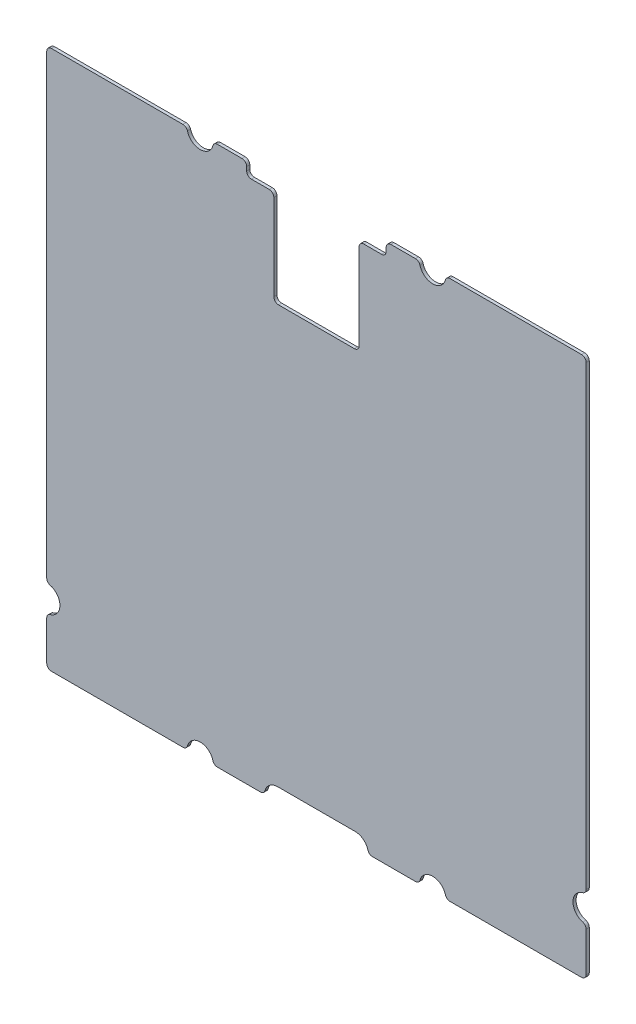
SolidWorks part; units mm, degrees
ref_plane "Front Plane" through (0, 0, 0) normal (0, 0, 1) x (1, 0, 0)
ref_plane "Top Plane" through (0, 0, 0) normal (0, 1, 0) x (1, 0, 0)
ref_plane "Right Plane" through (0, 0, 0) normal (1, 0, 0) x (0, 0, -1)
sketch "Sketch2" plane through (0, 0, 0) normal (0, 0, 1) x (1, 0, 0)
  line L0 (-25, -165.5) -> (25, -165.5)
  line L1 (-174, 174) -> (-83.5, 174)
  line L2 (-174, 174) -> (-174, -126)
  line L3 (-174, -174) -> (-83.5, -174)
  line L4 (174, 174) -> (174, -126)
  line L5 (-174, 174) -> (174, -174) construction
  line L6 (-174, -174) -> (174, 174) construction
  line L7 (33.5, -174) -> (66.5, -174)
  line L8 (-75, -174) -> (75, -174) construction
  line L9 (-66.5, -174) -> (-33.5, -174)
  line L10 (83.5, -174) -> (174, -174)
  line L11 (174, -143) -> (174, -174)
  line L12 (-174, -143) -> (-174, -174)
  line L13 (-66.5, 174) -> (-45, 174)
  line L14 (45, 174) -> (66.5, 174)
  line L15 (83.5, 174) -> (174, 174)
  line L16 (-27.5, 165.5) -> (-27.5, 104)
  line L17 (-25, -174) -> (25, -174) construction
  line L18 (-177.5, 177.5) -> (177.5, 177.5) construction
  line L19 (-177.5, 177.5) -> (-177.5, -177.5) construction
  line L20 (-177.5, -177.5) -> (177.5, -177.5) construction
  line L21 (177.5, 177.5) -> (177.5, -177.5) construction
  line L22 (-177.5, 177.5) -> (177.5, -177.5) construction
  line L23 (-177.5, -177.5) -> (177.5, 177.5) construction
  line L24 (-27.5, 104) -> (27.5, 104)
  line L25 (27.5, 104) -> (27.5, 165.5)
  line L26 (-27.5, 165.5) -> (-45, 165.5)
  line L27 (-45, 165.5) -> (-45, 174)
  line L28 (27.5, 165.5) -> (45, 165.5)
  line L29 (45, 165.5) -> (45, 174)
  arc A1 (66.5, 174) -> (83.5, 174) centre (75, 174) ccw
  arc A2 (-83.5, 174) -> (-66.5, 174) centre (-75, 174) ccw
  arc A3 (-66.5, -174) -> (-83.5, -174) centre (-75, -174) ccw
  arc A4 (-25, -165.5) -> (-33.5, -174) centre (-25, -174) ccw
  arc A5 (33.5, -174) -> (25, -165.5) centre (25, -174) ccw
  arc A6 (83.5, -174) -> (66.5, -174) centre (75, -174) ccw
  arc A7 (-174, -143) -> (-174, -126) centre (-174, -134.5) ccw
  arc A8 (174, -126) -> (174, -143) centre (174, -134.5) ccw
  point P0 (0, 0)
  point P6 (0, 104)
  point P9 (-45, 169.75)
  point P15 (0, -174)
  point P26 (0, 170.5)
  point P27 (0, -165.5)
  point P38 (0, 0)
  point P45 (-75, 165.5)
  dimension "D3" = 8.5
  dimension "D8" = 90
  dimension "D1" = 348
  dimension "D2" = 50
  dimension "D4" = 55
  dimension "D5" = 305
  dimension "D6" = 348
  dimension "D7" = 70
  dimension "D9" = 150
  dimension "D10" = 7
  dimension "D11" = 355
extrude "Boss-Extrude1" add sketch "Sketch2" along normal blind 2
fillet "Fillet1" radius 3 26 edges at (174, 174, 1) (83.5, 174, 1) (66.5, 174, 1) (27.5, 104, 1) (-27.5, 104, 1) (-66.5, 174, 1) (-83.5, 174, 1) (-174, 174, 1) (174, -126, 1) (174, -143, 1) (174, -174, 1) (83.5, -174, 1) (66.5, -174, 1) (-33.5, -174, 1) (33.5, -174, 1) (-66.5, -174, 1) (-83.5, -174, 1) (-174, -174, 1) (-174, -143, 1) (-174, -126, 1) (-45, 174, 1) (-45, 165.5, 1) (-27.5, 165.5, 1) (27.5, 165.5, 1) (45, 165.5, 1) (45, 174, 1)
